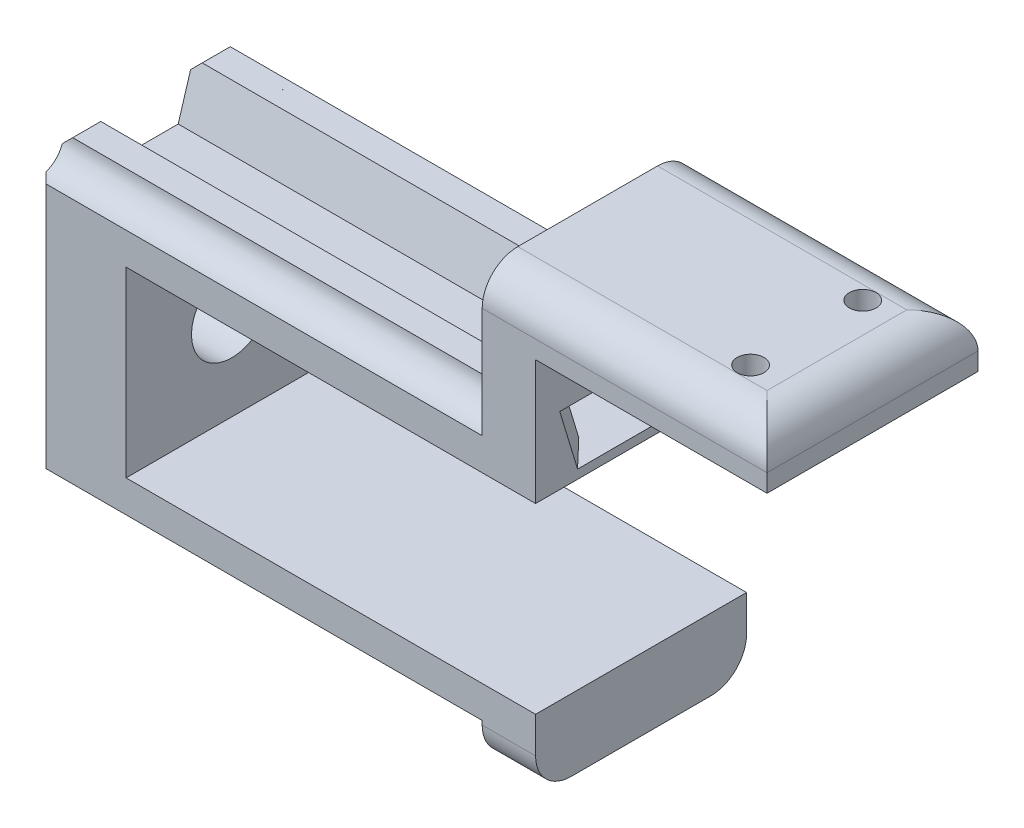
SolidWorks part; units mm, degrees
ref_plane "Front Plane" through (0, 0, 0) normal (0, 0, 1) x (1, 0, 0)
ref_plane "Top Plane" through (0, 0, 0) normal (0, 1, 0) x (1, 0, 0)
ref_plane "Right Plane" through (0, 0, 0) normal (1, 0, 0) x (0, 0, -1)
sketch "Sketch1" plane through (0, 0, 0) normal (1, 0, 0) x (0, 0, -1)
  line L0 (-5.925, 0) -> (5.925, 0) construction
  line L1 (-4.425, -8.425) -> (4.425, -8.425)
  line L2 (-5.925, -6.925) -> (-5.925, 6.925)
  line L3 (-4.425, 8.425) -> (4.425, 8.425)
  line L4 (5.925, -6.925) -> (5.925, 6.925)
  line L5 (0, 8.425) -> (0, -8.425) construction
  arc A1 (-5.925, 6.925) -> (-4.425, 8.425) centre (-5.925, 8.425) ccw
  arc A2 (4.425, 8.425) -> (5.925, 6.925) centre (5.925, 8.425) ccw
  arc A3 (-5.925, -6.925) -> (-4.425, -8.425) centre (-5.925, -8.425) cw
  arc A4 (5.925, -6.925) -> (4.425, -8.425) centre (5.925, -8.425) ccw
  point P0 (0, 0)
  point P16 (0, 0)
  dimension "D4" = 1.5
  dimension "D2" = 11.85
  dimension "D3" = 16.85
extrude "Boss-Extrude1" add sketch "Sketch1" along normal blind 25
sketch "Sketch2" plane through (0, 0, 0) normal (0, 0, 1) x (1, 0, 0)
  line L0 (25, 6.925) -> (25, -6.925) construction
  line L1 (25, 5.125) -> (5, 5.125)
  line L2 (25, 5.125) -> (25, -5.125)
  line L3 (25, -5.125) -> (5, -5.125)
  line L4 (5, 5.125) -> (5, -5.125)
  line L5 (0, 0) -> (5, 0) construction
  dimension "D1" = 10.25
  dimension "D2" = 20
extrude "Cut-Extrude1" cut sketch "Sketch2" against normal through all both and the other way through all
sketch "Sketch3" plane through (5, 0, 0) normal (1, 0, 0) x (0, 0, -1)
  circle A0 centre (0, 0) radius 2.25
  point P1 (0, 2.25)
  point P4 (-0.2128, -2.25)
  dimension "D1" = 4.5
extrude "Cut-Extrude2" cut sketch "Sketch3" against normal through all both
sketch "Sketch5" plane through (25, 0, 0) normal (1, 0, 0) x (0, 0, -1)
  line L0 (-5.925, 5.125) -> (5.925, 5.125)
  line L1 (-5.925, -9.15) -> (5.925, -9.15)
  line L2 (-5.925, -9.15) -> (-5.925, -5.125)
  line L3 (-5.925, 9.15) -> (5.925, 9.15) construction
  line L4 (5.925, -9.15) -> (5.925, -5.125)
  line L5 (0, -9.15) -> (0, 9.15) construction
  line L7 (5.925, 5.125) -> (-5.925, 5.125) construction
  line L8 (-5.925, -5.125) -> (5.925, -5.125)
  line L9 (5.925, -5.125) -> (-5.925, -5.125) construction
  line L10 (-5.925, -5.125) -> (-5.925, 5.125) construction
  line L11 (-5.925, 5.125) -> (-5.925, 9.15)
  line L12 (5.925, -5.125) -> (5.925, 5.125) construction
  line L13 (5.925, 5.125) -> (5.925, 9.15)
  line L14 (-5.925, 9.15) -> (-5.925, 15.125)
  line L15 (-5.925, 15.125) -> (5.925, 15.125)
  line L16 (5.925, 15.125) -> (5.925, 9.15)
  line L17 (-5.925, 6.925) -> (-5.925, 5.125) construction
  point P0 (0, 0)
  dimension "D1" = 18.3
  dimension "D3" = 10
extrude "Boss-Extrude2" add sketch "Sketch5" along normal blind 3
sketch "Sketch4" plane through (28, 0, 0) normal (1, 0, 0) x (0, 0, -1)
  line L1 (-3, 8.925) -> (3, 8.925)
  line L2 (-3, 8.925) -> (-2, 5.625)
  line L3 (-2, 5.625) -> (2, 5.625)
  line L4 (3, 8.925) -> (2, 5.625)
  line L5 (4.425, 8.425) -> (-4.425, 8.425) construction
  line L6 (0, 5.625) -> (0, 0) construction
  line L7 (-5.925, 5.125) -> (5.925, 5.125) construction
  line L8 (0, 5.625) -> (0, 8.925) construction
  dimension "D1" = 0.5
  dimension "D2" = 4
  dimension "D3" = 0.5
  dimension "D4" = 6
extrude "Cut-Extrude3" cut sketch "Sketch4" against normal through all both and the other way through all
sketch "Sketch6" plane through (0, 15.125, 0) normal (0, -1, 0) x (1, 0, 0)
  line L0 (32.2, -6.425) -> (29.5, 6.425) construction
  line L1 (32.2, -6.425) -> (38.5, -6.425) construction
  line L2 (32.2, -6.425) -> (32.2, 6.425) construction
  line L3 (32.2, 6.425) -> (38.5, 6.425) construction
  line L4 (38.5, -6.425) -> (38.5, 6.425) construction
  line L5 (38.5, 0) -> (32.2, 0) construction
  line L6 (37.3, -3.15) -> (37.3, 3.15) construction
  line L7 (32.2, -6.425) -> (28, 6.425) construction
  line L8 (28, -2) -> (28, 2) construction
  line L10 (25, 5.925) -> (41, 5.925)
  line L11 (25, 5.925) -> (25, -5.925)
  line L12 (25, -5.925) -> (41, -5.925)
  line L13 (41, 5.925) -> (41, -5.925)
  circle A0 centre (37.3, -3.15) radius 0.75
  circle A1 centre (37.3, 3.15) radius 0.75
  point P9 (37.3, 0)
  point P16 (25, -6.5)
  dimension "D6" = 1.5
  dimension "D1" = 9
  dimension "D2" = 6.3
  dimension "D3" = 12.85
  dimension "D4" = 5.1
  dimension "D5" = 6.3
  dimension "D7" = 10.5
  dimension "D8" = 16
extrude "Boss-Extrude3" add sketch "Sketch6" along normal blind 3
fillet "Fillet1" radius 2 5 edges at (26.5, -9.15, -5.925) (26.5, -9.15, 5.925) (33, 15.125, -5.925) (33, 15.125, 5.925) (41, 15.125, 0)
chamfer "Chamfer1" distance 1.5 angle 45 2 edges at (28, 7.275, 2.5) (28, 7.275, -2.5)
chamfer "Chamfer2" distance 0.5 angle 45 5 edges at (0, -8.425, 0) (0, 0, -5.925) (0, 0, 5.925) (0, 8.425, 3.6367) (0, 8.425, -3.6367)
equation "\"D3@Sketch5\"=6+1+3"
